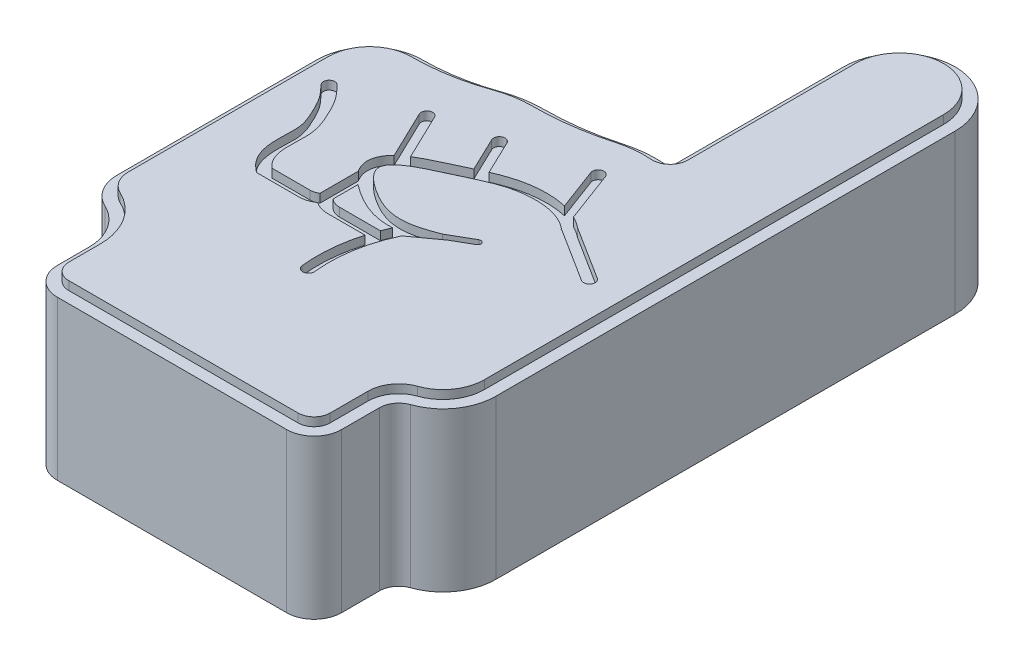
SolidWorks part; units mm, degrees
ref_plane "Plan de face" through (0, 0, 0) normal (0, 0, 1) x (1, 0, 0)
ref_plane "Plan de dessus" through (0, 0, 0) normal (0, 1, 0) x (1, 0, 0)
ref_plane "Plan de droite" through (0, 0, 0) normal (1, 0, 0) x (0, 0, -1)
sketch "Esquisse2" plane through (0, 0, 0) normal (0, 1, 0) x (1, 0, 0)
  line L4 (-461.3514, 50.6784) -> (-461.3514, 90.7755)
  line L5 (-471.0713, 90.7755) -> (-471.0713, 76.1755)
  line L6 (-465.5648, 44.7364) -> (-465.5648, 41.4326)
  line L7 (-467.9625, 39.035) -> (-487.9825, 39.035)
  line L8 (-490.3801, 41.4326) -> (-490.3801, 44.1985)
  line L9 (-494.5966, 50.8393) -> (-494.5966, 68.3008)
  arc A17 (-461.3514, 90.7755) -> (-471.0713, 90.7755) centre (-466.2114, 90.7755) ccw
  arc A18 (-471.0713, 76.1755) -> (-471.6659, 75.6215) centre (-471.6268, 76.1755) cw
  arc A19 (-471.6659, 75.6215) -> (-474.8438, 75.3021) centre (-472.3289, 66.2484) ccw
  arc A20 (-461.3514, 50.6784) -> (-464.4333, 46.3321) centre (-465.9571, 50.6784) cw
  arc A21 (-464.4333, 46.3321) -> (-465.5648, 44.7364) centre (-463.8739, 44.7364) ccw
  arc A22 (-465.5648, 41.4326) -> (-467.9625, 39.035) centre (-467.9625, 41.4326) cw
  arc A23 (-487.9825, 39.035) -> (-490.3801, 41.4326) centre (-487.9825, 41.4326) cw
  arc A24 (-490.3801, 44.1985) -> (-492.803, 48.0144) centre (-494.5966, 44.1985) ccw
  arc A25 (-492.803, 48.0144) -> (-494.5966, 50.8393) centre (-491.4751, 50.8393) cw
  arc A26 (-494.5966, 68.3008) -> (-489.9856, 72.9117) centre (-489.9856, 68.3008) cw
  arc A27 (-489.9856, 72.9117) -> (-484.1893, 73.9115) centre (-489.9856, 90.214) ccw
  arc A28 (-484.1893, 73.9115) -> (-480.9635, 74.4679) centre (-480.9635, 64.8387) cw
  arc A29 (-480.9635, 74.4679) -> (-474.8438, 75.3021) centre (-480.9635, 97.3326) ccw
  dimension "D3" = 14.6
  dimension "D4" = 0.5554
  dimension "D5" = 9.3965
  dimension "D6" = 4.6057
  dimension "D7" = 1.6909
  dimension "D8" = 2.3977
  dimension "D9" = 4.2164
  dimension "D10" = 3.1214
  dimension "D11" = 4.6109
  dimension "D12" = 17.3023
  dimension "D13" = 9.6292
  dimension "D1" = 9.72
  dimension "D2" = 461.3514
  dimension "D15" = 472.3289
  dimension "D16" = 465.5648
  dimension "D17" = 480.9635
  dimension "D18" = 484.1893
  dimension "D19" = 72.9117
  dimension "D21" = 50.8393
  dimension "D22" = 50.6784
  dimension "D36" = 39.035
extrude "Boss.-Extru.1" add sketch "Esquisse2" along normal blind 14.6
sketch "Esquisse4" plane through (0, 14.6, 0) normal (0, 1, 0) x (1, 0, 0)
  line L0 (-472.4313, 71.3413) -> (-470.759, 66.8763)
  line L1 (-479.2673, 69.577) -> (-477.8287, 66.5691)
  line L2 (-484.8272, 68.1421) -> (-483.1754, 64.6884)
  line L3 (-487.6052, 57.4055) -> (-484.2817, 57.4055)
  line L5 (-478.1514, 57.4055) -> (-481.7388, 57.4055)
  line L6 (-490.4583, 65.8897) -> (-491.0481, 66.5366)
  line L7 (-491.0481, 66.5366) -> (-472.4313, 71.3413) construction
  line L8 (-461.3514, 50.6784) -> (-461.3514, 90.7755) construction
  line L9 (-473.3677, 70.9906) -> (-471.9932, 67.3203)
  line L10 (-480.1694, 69.1456) -> (-478.7397, 66.1562)
  line L12 (-491.1972, 65.2159) -> (-491.787, 65.8628)
  line L13 (-487.9601, 56.4055) -> (-484.2783, 56.4055)
  line L14 (-477.4426, 56.4055) -> (-481.7388, 56.4055)
  line L16 (-483.1205, 57.4055) -> (-483.1205, 61.028) construction
  line L17 (-483.6205, 57.5979) -> (-483.6205, 60.9564)
  line L18 (-484.8272, 68.1421) -> (-482.7323, 63.7919) construction
  line L19 (-484.3767, 68.359) -> (-482.4341, 64.3251)
  line L20 (-485.2777, 67.9251) -> (-483.2443, 63.7026)
  line L21 (-470.3753, 65.4409) -> (-465.3514, 62.8537) construction
  line L22 (-469.8136, 66.2662) -> (-465.0842, 63.2763)
  line L23 (-470.348, 65.421) -> (-465.6185, 62.4311)
  line L24 (-473.0349, 60.7918) -> (-475.4776, 59.3877) construction
  line L25 (-472.8992, 60.5556) -> (-474.5084, 59.6306)
  line L26 (-473.1707, 61.028) -> (-475.2006, 59.8612)
  line L27 (-482.6205, 57.7552) -> (-482.6205, 59.9234)
  arc A0 (-484.2817, 57.4055) -> (-483.6205, 57.5979) centre (-484.2916, 58.6719) ccw
  arc A1 (-476.8297, 57.9491) -> (-477.9359, 51.4698) centre (-466.0442, 52.7736) ccw
  arc A3 (-481.7388, 57.4055) -> (-482.6205, 57.7552) centre (-481.7388, 58.692) cw
  arc A5 (-484.2783, 56.4055) -> (-483.0183, 56.797) centre (-484.2916, 58.6719) ccw
  arc A6 (-481.7388, 56.4055) -> (-483.0183, 56.797) centre (-481.7388, 58.692) cw
  arc A7 (-477.8343, 58.1619) -> (-478.1514, 57.4055) centre (-466.0442, 52.7736) ccw
  arc A8 (-472.4313, 71.3413) -> (-473.3677, 70.9906) centre (-472.8995, 71.1659) ccw
  arc A10 (-479.2673, 69.577) -> (-480.1694, 69.1456) centre (-479.7183, 69.3613) ccw
  arc A14 (-491.0481, 66.5366) -> (-491.787, 65.8628) centre (-491.4176, 66.1997) ccw
  arc A18 (-470.4025, 65.4609) -> (-470.348, 65.421) centre (-470.3753, 65.4409) ccw
  arc A19 (-477.9359, 51.4698) -> (-478.93, 51.3609) centre (-478.433, 51.4154) cw
  arc A21 (-484.3767, 68.359) -> (-485.2777, 67.9251) centre (-484.8272, 68.1421) ccw
  arc A23 (-470.4025, 65.4609) -> (-470.348, 65.421) centre (-470.3753, 65.4409) ccw
  arc A24 (-465.6185, 62.4311) -> (-465.0842, 63.2763) centre (-465.3514, 62.8537) ccw
  arc A25 (-472.8992, 60.5556) -> (-473.1707, 61.028) centre (-473.0349, 60.7918) ccw
  arc A27 (-478.488, 56.4055) -> (-478.93, 51.3609) centre (-466.0442, 52.7736) ccw
  spline S0 degree 3 poles (-490.4583, 65.8897) (-489.9643, 65.3478) (-489.2576, 64.0084) (-488.0431, 61.1753) (-489.0579, 58.5852) (-487.6052, 57.4055) knots 0 0 0 0 0.249547 0.474449 1 1 1 1
  spline S1 degree 3 poles (-483.1823, 64.7264) (-483.18, 64.7137) (-483.1777, 64.7011) (-483.1754, 64.6884) knots 0.246141 0.246141 0.246141 0.246141 0.248714 0.248714 0.248714 0.248714
  spline S2 degree 3 poles (-470.4025, 65.4609) (-471.657, 66.5152) (-475.3225, 66.8063) (-478.8719, 64.9069) (-484.364, 62.5575) (-480.7126, 59.6038) (-478.2259, 58.8088) (-475.901, 59.5831) (-475.2006, 59.8612) knots 0 0 0 0 0.163612 0.32751 0.477242 0.563601 0.697734 0.765481 0.765481 0.765481 0.765481
  spline S3 degree 2 poles (-474.5084, 59.6306) (-475.3996, 58.9745) (-476.8297, 57.9491) knots 0.955294 0.955294 0.955294 1 1 1
  spline S4 degree 3 poles (-483.2443, 63.7026) (-483.4189, 63.536) (-483.7603, 63.1422) (-484.042, 62.4144) (-483.9809, 61.7052) (-483.8197, 61.2849) (-483.6856, 61.0541) (-483.6205, 60.9564) knots 0.428302 0.428302 0.428302 0.428302 0.447364 0.468667 0.479319 0.48997 0.498689 0.498689 0.498689 0.498689
  spline S5 degree 3 poles (-478.7397, 66.1562) (-478.841, 66.109) (-479.3545, 65.8687) (-480.3361, 65.4112) (-481.5724, 64.8367) (-482.2436, 64.4471) (-482.4341, 64.3251) knots 0.287644 0.287644 0.287644 0.287644 0.298243 0.340849 0.383455 0.401257 0.401257 0.401257 0.401257
  spline S6 degree 3 poles (-491.1972, 65.2159) (-491.0951, 65.1039) (-490.914, 64.8749) (-490.5473, 64.3017) (-490.1129, 63.4322) (-489.672, 62.4162) (-489.5049, 61.5865) (-489.5458, 60.4567) (-489.5779, 59.3459) (-489.4093, 58.37) (-489.1649, 57.7435) (-488.8551, 57.2619) (-488.58, 56.9296) (-488.2037, 56.5974) (-488.0493, 56.478) (-487.9601, 56.4055) knots 0 0 0 0 0.064576 0.129153 0.258306 0.387458 0.516611 0.645764 0.774917 0.839493 0.90407 0.936358 0.968646 1.000934 1.033223 1.033223 1.033223 1.033223
  spline S7 degree 3 poles (-471.9932, 67.3203) (-472.1805, 67.365) (-473.344, 67.5872) (-475.4797, 67.4725) (-477.0435, 66.9088) (-477.8287, 66.5691) knots 0.068798 0.068798 0.068798 0.068798 0.085212 0.170424 0.255222 0.255222 0.255222 0.255222
  spline S8 degree 3 poles (-469.7591, 66.2264) (-470.0622, 66.4812) (-470.4037, 66.6993) (-470.759, 66.8763) knots 0 0 0 0 0.03228 0.03228 0.03228 0.03228
  spline S9 degree 3 poles (-482.6205, 59.9234) (-482.4376, 59.7779) (-481.8068, 59.3219) (-480.7516, 58.706) (-479.3663, 58.2092) (-478.3366, 58.1325) (-477.8343, 58.1619) knots 0.535686 0.535686 0.535686 0.535686 0.553879 0.596485 0.639091 0.681698 0.681698 0.681698 0.681698
  point P38 (-483.7797, 65.967)
  point P58 (-483.1205, 59.2167)
  point P61 (-474.2563, 60.0898)
  point P67 (-467.7161, 64.3487)
  dimension "D4" = 1.2865
  dimension "D6" = 4.6928
  dimension "D9" = 2.2865
  dimension "D10" = 11.0799
  dimension "D11" = 11.1625
  dimension "D13" = 13.661
  dimension "D1" = 1.2664
  dimension "D2" = 11.963
  dimension "D5" = 0.5
  dimension "D7" = 2.2664
  dimension "D12" = 0.0338
  dimension "D15" = 0.2724
  dimension "D8" = 1
  dimension "D14" = 15.4783
  dimension "D16" = 16.0443
  dimension "D17" = 3.7328
  dimension "D18" = 16.5846
  dimension "D19" = 17.9159
  dimension "D20" = 18.1649
  dimension "D21" = 1
  dimension "D22" = 20.3874
  dimension "D23" = 21.6423
  dimension "D24" = 4
  dimension "D25" = 21.824
  dimension "D26" = 5.1377
  dimension "D27" = 4.2671
  dimension "D28" = 23.4758
  dimension "D29" = 26.2538
  dimension "D30" = 27.0797
  dimension "D31" = 27.2299
  dimension "D32" = 27.9056
  dimension "D33" = 29.1069
  dimension "D34" = 29.6967
  dimension "D35" = 12.8812
  dimension "D36" = 13.8294
  dimension "D37" = 6.3647
  dimension "D38" = 8.4077
  dimension "D39" = 17.6054
  dimension "D40" = 18.3562
  dimension "D41" = 8.4623
  dimension "D42" = 9.0239
  dimension "D43" = 19.5575
  dimension "D44" = 11.5481
  dimension "D45" = 16.0912
  dimension "D46" = 9.4077
  dimension "D47" = 10.6418
  dimension "D48" = 11.5478
  dimension "D49" = 18.3669
  dimension "D50" = 11.6836
  dimension "D51" = 11.8193
  dimension "D52" = 21.2691
  dimension "D53" = 12.9049
  dimension "D54" = 13.157
  dimension "D55" = 13.8492
  dimension "D56" = 21.6669
  dimension "D57" = 16.4773
  dimension "D58" = 16.4829
  dimension "D59" = 23.0253
  dimension "D60" = 30.0662
  dimension "D61" = 12.8846
  dimension "D62" = 17.3883
  dimension "D63" = 16.099
  dimension "D64" = 12.3497
  dimension "D65" = 18.3943
  dimension "D66" = 19.8742
  dimension "D67" = 21.0827
  dimension "D70" = 21.7691
  dimension "D71" = 21.8309
  dimension "D72" = 21.8929
  dimension "D73" = 13.5913
  dimension "D74" = 22.4283
  dimension "D75" = 13.7576
  dimension "D79" = 15.6533
  dimension "D80" = 26.6087
  dimension "D84" = 18.0165
  dimension "D90" = 19.8943
  dimension "D92" = 20.076
extrude "Cut-Extrude1" cut sketch "Esquisse4" against normal blind 0.75
sketch "Sketch1" plane through (0, 14.6, 0) normal (0, 1, 0) x (1, 0, 0)
  line L0 (-462.3514, 50.6784) -> (-462.3514, 90.7755)
  line L1 (-470.0713, 90.7755) -> (-470.0713, 76.1755)
  line L2 (-493.5966, 68.3008) -> (-493.5966, 50.8393)
  line L3 (-489.3801, 44.1985) -> (-489.3801, 41.4326)
  line L4 (-487.9825, 40.035) -> (-467.9625, 40.035)
  line L5 (-466.5648, 41.4326) -> (-466.5648, 44.7364)
  line L6 (-461.3514, 50.6784) -> (-461.3514, 90.7755)
  line L7 (-471.0713, 90.7755) -> (-471.0713, 76.1755)
  line L8 (-494.5966, 68.3008) -> (-494.5966, 50.8393)
  line L9 (-490.3801, 44.1985) -> (-490.3801, 41.4326)
  line L10 (-487.9825, 39.035) -> (-467.9625, 39.035)
  line L11 (-465.5648, 41.4326) -> (-465.5648, 44.7364)
  line L12 (-461.3514, 50.6784) -> (-461.3514, 90.7755)
  line L13 (-471.0713, 90.7755) -> (-471.0713, 76.1755)
  line L14 (-494.5966, 68.3008) -> (-494.5966, 50.8393)
  line L15 (-490.3801, 44.1985) -> (-490.3801, 41.4326)
  line L16 (-487.9825, 39.035) -> (-467.9625, 39.035)
  line L17 (-465.5648, 41.4326) -> (-465.5648, 44.7364)
  arc A0 (-464.7642, 47.2758) -> (-462.3514, 50.6784) centre (-465.9571, 50.6784) ccw
  arc A1 (-462.3514, 90.7755) -> (-470.0713, 90.7755) centre (-466.2114, 90.7755) ccw
  arc A2 (-471.7365, 74.624) -> (-470.0713, 76.1755) centre (-471.6268, 76.1755) ccw
  arc A3 (-471.7365, 74.624) -> (-474.5762, 74.3386) centre (-472.3289, 66.2484) ccw
  arc A4 (-480.9635, 73.4679) -> (-474.5762, 74.3386) centre (-480.9635, 97.3326) ccw
  arc A5 (-480.9635, 73.4679) -> (-483.8543, 72.9693) centre (-480.9635, 64.8387) ccw
  arc A6 (-489.9856, 71.9117) -> (-483.8543, 72.9693) centre (-489.9856, 90.214) ccw
  arc A7 (-489.9856, 71.9117) -> (-493.5966, 68.3008) centre (-489.9856, 68.3008) ccw
  arc A8 (-493.5966, 50.8393) -> (-492.3776, 48.9194) centre (-491.4751, 50.8393) ccw
  arc A9 (-489.3801, 44.1985) -> (-492.3776, 48.9194) centre (-494.5966, 44.1985) ccw
  arc A10 (-489.3801, 41.4326) -> (-487.9825, 40.035) centre (-487.9825, 41.4326) ccw
  arc A11 (-467.9625, 40.035) -> (-466.5648, 41.4326) centre (-467.9625, 41.4326) ccw
  arc A12 (-464.7642, 47.2758) -> (-466.5648, 44.7364) centre (-463.8739, 44.7364) ccw
  arc A13 (-464.4333, 46.3321) -> (-461.3514, 50.6784) centre (-465.9571, 50.6784) ccw
  arc A14 (-461.3514, 90.7755) -> (-471.0713, 90.7755) centre (-466.2114, 90.7755) ccw
  arc A15 (-471.6659, 75.6215) -> (-471.0713, 76.1755) centre (-471.6268, 76.1755) ccw
  arc A16 (-471.6659, 75.6215) -> (-474.8438, 75.3021) centre (-472.3289, 66.2484) ccw
  arc A17 (-480.9635, 74.4679) -> (-474.8438, 75.3021) centre (-480.9635, 97.3326) ccw
  arc A18 (-480.9635, 74.4679) -> (-484.1893, 73.9115) centre (-480.9635, 64.8387) ccw
  arc A19 (-489.9856, 72.9117) -> (-484.1893, 73.9115) centre (-489.9856, 90.214) ccw
  arc A20 (-489.9856, 72.9117) -> (-494.5966, 68.3008) centre (-489.9856, 68.3008) ccw
  arc A21 (-494.5966, 50.8393) -> (-492.803, 48.0144) centre (-491.4751, 50.8393) ccw
  arc A22 (-490.3801, 44.1985) -> (-492.803, 48.0144) centre (-494.5966, 44.1985) ccw
  arc A23 (-490.3801, 41.4326) -> (-487.9825, 39.035) centre (-487.9825, 41.4326) ccw
  arc A24 (-467.9625, 39.035) -> (-465.5648, 41.4326) centre (-467.9625, 41.4326) ccw
  arc A25 (-464.4333, 46.3321) -> (-465.5648, 44.7364) centre (-463.8739, 44.7364) ccw
  arc A26 (-464.4333, 46.3321) -> (-461.3514, 50.6784) centre (-465.9571, 50.6784) ccw
  arc A27 (-461.3514, 90.7755) -> (-471.0713, 90.7755) centre (-466.2114, 90.7755) ccw
  arc A28 (-471.6659, 75.6215) -> (-471.0713, 76.1755) centre (-471.6268, 76.1755) ccw
  arc A29 (-471.6659, 75.6215) -> (-474.8438, 75.3021) centre (-472.3289, 66.2484) ccw
  arc A30 (-480.9635, 74.4679) -> (-474.8438, 75.3021) centre (-480.9635, 97.3326) ccw
  arc A31 (-480.9635, 74.4679) -> (-484.1893, 73.9115) centre (-480.9635, 64.8387) ccw
  arc A32 (-489.9856, 72.9117) -> (-484.1893, 73.9115) centre (-489.9856, 90.214) ccw
  arc A33 (-489.9856, 72.9117) -> (-494.5966, 68.3008) centre (-489.9856, 68.3008) ccw
  arc A34 (-494.5966, 50.8393) -> (-492.803, 48.0144) centre (-491.4751, 50.8393) ccw
  arc A35 (-490.3801, 44.1985) -> (-492.803, 48.0144) centre (-494.5966, 44.1985) ccw
  arc A36 (-490.3801, 41.4326) -> (-487.9825, 39.035) centre (-487.9825, 41.4326) ccw
  arc A37 (-467.9625, 39.035) -> (-465.5648, 41.4326) centre (-467.9625, 41.4326) ccw
  arc A38 (-464.4333, 46.3321) -> (-465.5648, 44.7364) centre (-463.8739, 44.7364) ccw
  dimension "D1" = 0
  dimension "D2" = 1
extrude "Cut-Extrude2" cut sketch "Sketch1" against normal blind 0.75
